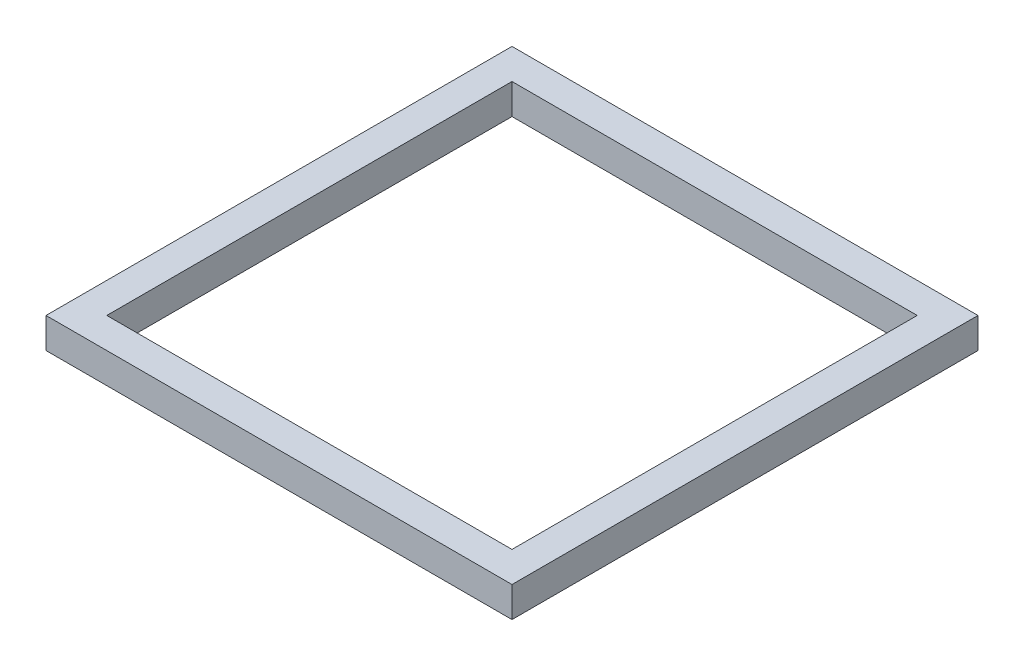
SolidWorks part; units mm, degrees
ref_plane "前视基准面" through (0, 0, 0) normal (0, 0, 1) x (1, 0, 0)
ref_plane "上视基准面" through (0, 0, 0) normal (0, 1, 0) x (1, 0, 0)
ref_plane "右视基准面" through (0, 0, 0) normal (1, 0, 0) x (0, 0, -1)
sketch "草图1" plane through (0, 0, 0) normal (0, 1, 0) x (1, 0, 0)
  line L1 (-100, 100) -> (100, 100)
  line L2 (-100, 100) -> (-100, -100)
  line L3 (-100, -100) -> (100, -100)
  line L4 (100, 100) -> (100, -100)
  line L5 (-100, 100) -> (100, -100) construction
  line L6 (-100, -100) -> (100, 100) construction
  line L7 (-115, 115) -> (115, 115)
  line L8 (-115, 115) -> (-115, -115)
  line L9 (-115, -115) -> (115, -115)
  line L10 (115, 115) -> (115, -115)
  line L11 (-115, 115) -> (115, -115) construction
  line L12 (-115, -115) -> (115, 115) construction
  point P0 (0, 0)
  point P6 (0, 0)
  dimension "D1" = 200
  dimension "D2" = 200
  dimension "D3" = 15
  dimension "D4" = 15
extrude "凸台-拉伸1" add sketch "草图1" along normal blind 15
